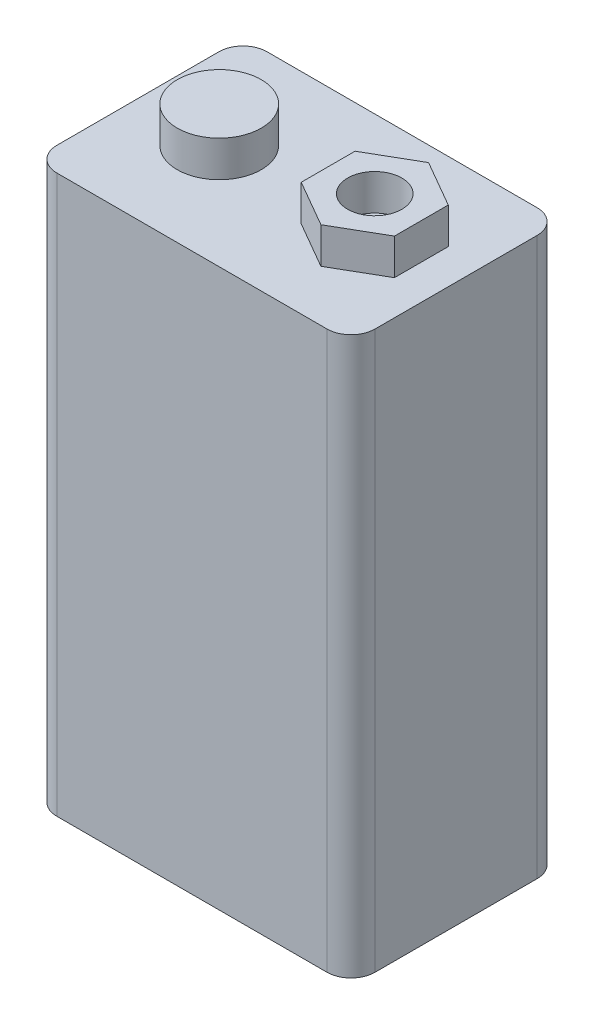
SolidWorks part; units mm, degrees
material "AISI 304"
ref_plane "Front Plane" through (0, 0, 0) normal (0, 0, 1) x (1, 0, 0)
ref_plane "Top Plane" through (0, 0, 0) normal (0, 1, 0) x (1, 0, 0)
ref_plane "Right Plane" through (0, 0, 0) normal (1, 0, 0) x (0, 0, -1)
sketch "Sketch1" plane through (0, 0, 0) normal (0, 1, 0) x (1, 0, 0)
  line L1 (-11.25, -8.75) -> (11.25, -8.75)
  line L2 (-13.25, -6.75) -> (-13.25, 6.75)
  line L3 (-11.25, 8.75) -> (11.25, 8.75)
  line L4 (13.25, -6.75) -> (13.25, 6.75)
  line L5 (-13.25, -8.75) -> (13.25, 8.75) construction
  line L6 (-13.25, 8.75) -> (13.25, -8.75) construction
  arc A0 (11.25, -8.75) -> (13.25, -6.75) centre (11.25, -6.75) ccw
  arc A1 (-11.25, -8.75) -> (-13.25, -6.75) centre (-11.25, -6.75) cw
  arc A2 (11.25, 8.75) -> (13.25, 6.75) centre (11.25, 6.75) cw
  arc A3 (-13.25, 6.75) -> (-11.25, 8.75) centre (-11.25, 6.75) cw
  point P0 (0, 0)
  dimension "D3" = 2
  dimension "D1" = 17.5
  dimension "D2" = 26.5
extrude "Boss-Extrude1" add sketch "Sketch1" along normal blind 46.4
sketch "Sketch2" plane through (0, 46.4, 0) normal (0, 1, 0) x (1, 0, 0)
  line L0 (-6.475, 0) -> (6.475, 0)
  line L2 (6.475, 4.4819) -> (2.5935, 2.241)
  line L3 (2.5935, 2.241) -> (2.5935, -2.241)
  line L4 (2.5935, -2.241) -> (6.475, -4.4819)
  line L5 (6.475, -4.4819) -> (10.3565, -2.241)
  line L6 (10.3565, -2.241) -> (10.3565, 2.241)
  line L7 (10.3565, 2.241) -> (6.475, 4.4819)
  circle A0 centre (-6.475, 0) radius 3.5
  circle A1 centre (6.475, 0) radius 2.2593
  circle A2 centre (6.475, 0) radius 3.8815 construction
  point P4 (0, 0)
  point P7 (6.475, 4.4819)
  dimension "D2" = 7
  dimension "D1" = 12.95
extrude "Boss-Extrude2" add sketch "Sketch2" along normal blind 3
